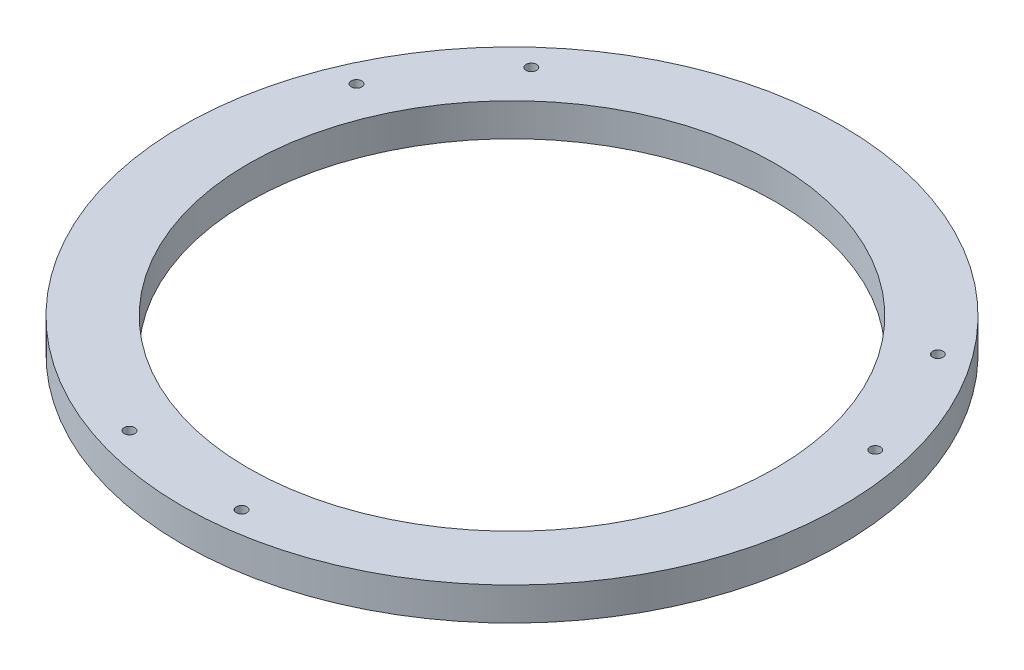
SolidWorks part; units mm, degrees
ref_plane "前视基准面" through (0, 0, 0) normal (0, 0, 1) x (1, 0, 0)
ref_plane "上视基准面" through (0, 0, 0) normal (0, 1, 0) x (1, 0, 0)
ref_plane "右视基准面" through (0, 0, 0) normal (1, 0, 0) x (0, 0, -1)
sketch "草图1" plane through (0, 0, 0) normal (0, 1, 0) x (1, 0, 0)
  circle A0 centre (0, 0) radius 100
  circle A1 centre (0, 0) radius 80
  dimension "D1" = 200
  dimension "D2" = 160
extrude "凸台-拉伸1" add sketch "草图1" along normal blind 10
sketch "草图3" plane through (0, 10, 0) normal (0, 1, 0) x (1, 0, 0)
  circle A0 centre (-62.3926, 68.2526) radius 1.6
  circle A1 centre (-84.5734, 37.3978) radius 1.6
extrude "切除-拉伸2" cut sketch "草图3" against normal through all
sketch "草图4" plane through (0, 0, 0) normal (0, -1, 0) x (1, 0, 0)
  line L0 (-80.8771, -38.8183) -> (-83.1528, -33.7016)
  line L1 (-85.9939, -41.0941) -> (-88.2696, -35.9773)
  line L2 (-83.1528, -33.7016) -> (-88.2696, -35.9773)
  line L3 (-80.8771, -38.8183) -> (-85.9939, -41.0941)
  line L4 (-62.1262, -72.2034) -> (-66.3434, -68.519)
  line L5 (-66.3434, -68.519) -> (-62.659, -64.3017)
  line L6 (-62.659, -64.3017) -> (-58.4418, -67.9861)
  line L7 (-58.4418, -67.9861) -> (-62.1262, -72.2034)
  circle A0 centre (-84.5734, -37.3978) radius 2.8 construction
  circle A1 centre (-62.3926, -68.2526) radius 2.8 construction
  point P13 (-66.3434, -68.519)
  dimension "D1" = 5.6
  dimension "D2" = 5.6
  dimension "D3" = 90
  dimension "D4" = 90
  dimension "D5" = 90
  dimension "D6" = 90
extrude "切除-拉伸3" cut sketch "草图4" against normal blind 3
pattern_circular "阵列(圆周)1" count 3 over 360 about axis through (0, 0, 0) along (0, 1, 0) of "切除-拉伸2", "切除-拉伸3"
